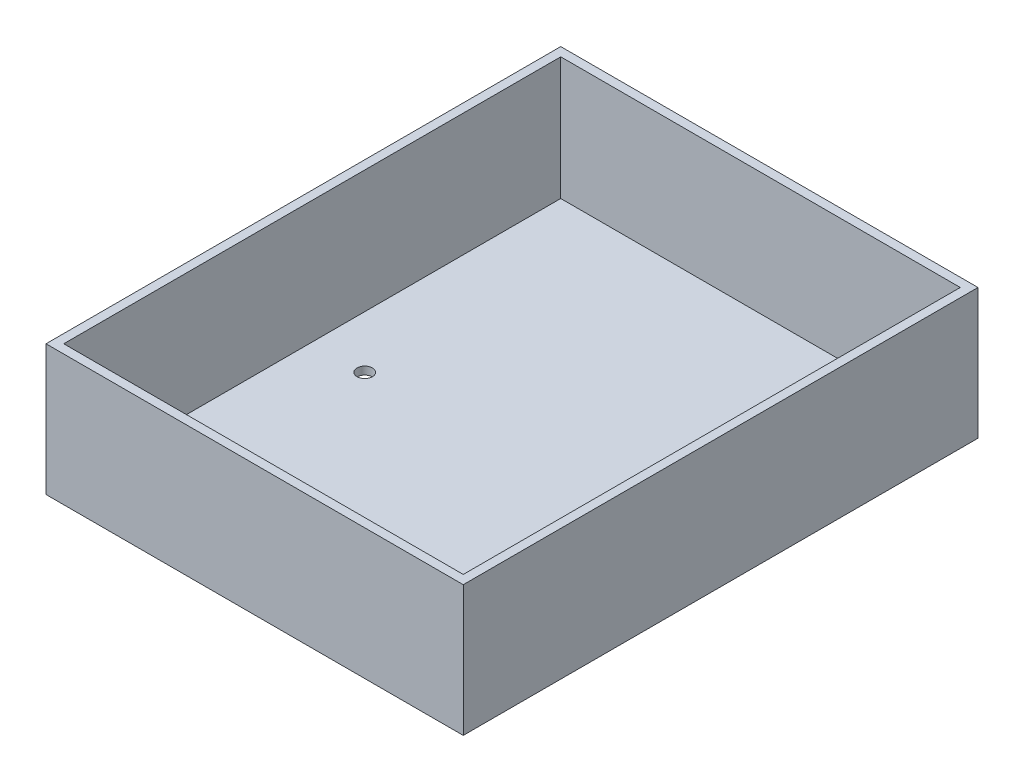
SolidWorks part; units mm, degrees
ref_plane "Front Plane" through (0, 0, 0) normal (0, 0, 1) x (1, 0, 0)
ref_plane "Top Plane" through (0, 0, 0) normal (0, 1, 0) x (1, 0, 0)
ref_plane "Right Plane" through (0, 0, 0) normal (1, 0, 0) x (0, 0, -1)
sketch "Sketch1" plane through (0, 0, 0) normal (0, 1, 0) x (1, 0, 0)
  line L1 (-30.6, 37.75) -> (30.6, 37.75)
  line L2 (-30.6, 37.75) -> (-30.6, -37.75)
  line L3 (-30.6, -37.75) -> (30.6, -37.75)
  line L4 (30.6, 37.75) -> (30.6, -37.75)
  line L5 (-30.6, 37.75) -> (30.6, -37.75) construction
  line L6 (-30.6, -37.75) -> (30.6, 37.75) construction
  point P0 (0, 0)
  dimension "D1" = 75.5
  dimension "D2" = 61.2
extrude "Boss-Extrude1" add sketch "Sketch1" along normal blind 19.15
sketch "Sketch2" plane through (0, 19.15, 0) normal (0, 1, 0) x (1, 0, 0)
  line L1 (-29.3, 36.4497) -> (29.3, 36.4497)
  line L2 (-29.3, 36.4497) -> (-29.3, -36.4497)
  line L3 (-29.3, -36.4497) -> (29.3, -36.4497)
  line L4 (29.3, 36.4497) -> (29.3, -36.4497)
  line L5 (-29.3, 36.4497) -> (29.3, -36.4497) construction
  line L6 (-29.3, -36.4497) -> (29.3, 36.4497) construction
  line L7 (-30.6, 37.75) -> (-30.6, -37.75) construction
  point P0 (0, 0)
  dimension "D1" = 1.3
extrude "Cut-Extrude1" cut sketch "Sketch2" against normal blind 18
sketch "Sketch3" plane through (0, 1.15, 0) normal (0, 1, 0) x (1, 0, 0)
  line L0 (30.6, 37.75) -> (-30.6, 37.75) construction
  line L1 (-30.6, 37.75) -> (-30.6, -37.75) construction
  line L2 (30.6, -37.75) -> (30.6, 37.75) construction
  circle A0 centre (-21.6, 0) radius 1.125
  circle A1 centre (21.6, 0) radius 1.125
  dimension "D1" = 37.75
  dimension "D3" = 37.75
  dimension "D2" = 9
  dimension "D4" = 9
extrude "Cut-Extrude2" cut sketch "Sketch3" against normal blind 20
